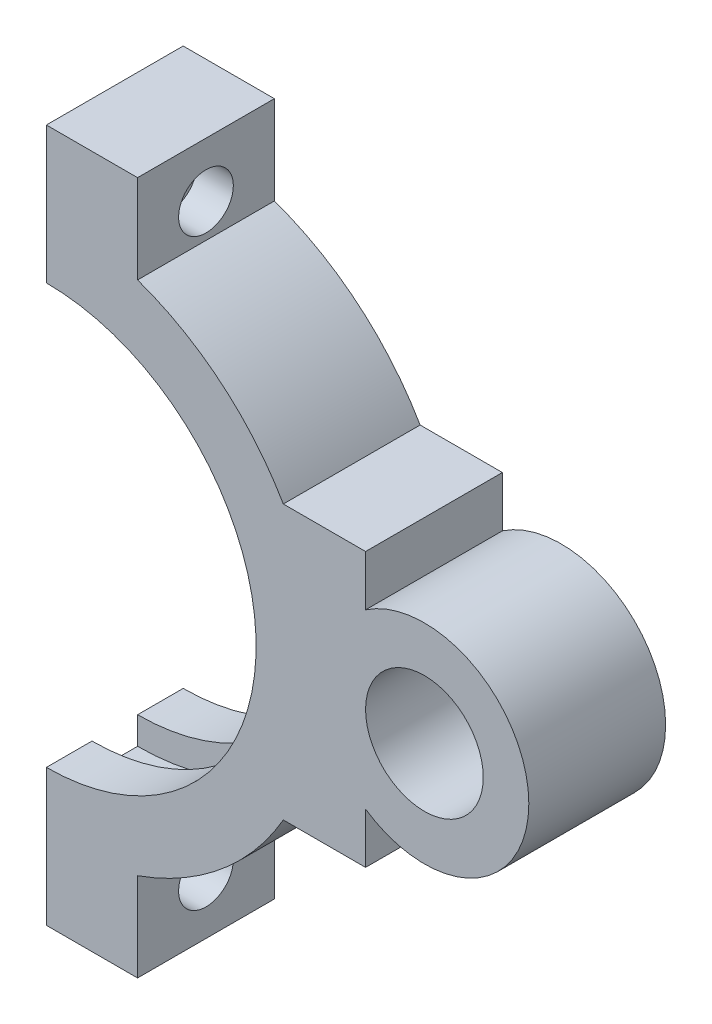
SolidWorks part; units mm, degrees
ref_plane "Front Plane" through (0, 0, 0) normal (0, 0, 1) x (1, 0, 0)
ref_plane "Top Plane" through (0, 0, 0) normal (0, 1, 0) x (1, 0, 0)
ref_plane "Right Plane" through (0, 0, 0) normal (1, 0, 0) x (0, 0, -1)
sketch "Sketch1" plane through (0, 0, 0) normal (0, 0, 1) x (1, 0, 0)
  line L0 (0, 26.4851) -> (0, 30.4851)
  line L1 (0, -25.5149) -> (0, -29.5149)
  line L2 (30, 15.4851) -> (30, -14.5149) construction
  line L3 (25.9808, 15.4851) -> (35, 15.4851)
  line L4 (25.9808, -14.5149) -> (35, -14.5149)
  line L5 (0, 0.4851) -> (66.6758, 0.4851) construction
  line L6 (35, 15.4851) -> (35, -14.5149) construction
  line L7 (35, -14.5149) -> (35, -8.9754)
  line L8 (35, 9.9455) -> (35, 15.4851)
  line L9 (0, 30.4851) -> (0, 38.4851)
  line L10 (0, 38.4851) -> (10, 38.4851)
  line L11 (10, 38.4851) -> (10, 28.7693)
  line L12 (10, -37.5149) -> (10, -27.7992)
  line L13 (0, -37.5149) -> (10, -37.5149)
  line L14 (0, -29.5149) -> (0, -37.5149)
  arc A0 (0, 26.4851) -> (0, -25.5149) centre (0, 0.4851) cw
  arc A1 (10, 28.7693) -> (25.9808, 15.4851) centre (0, 0.4851) cw
  arc A2 (25.9808, -14.5149) -> (10, -27.7992) centre (0, 0.4851) cw
  arc A3 (41.45, 6.9351) -> (41.45, -5.9649) centre (41.45, 0.4851) ccw
  arc A4 (41.45, 6.9351) -> (41.45, -5.9649) centre (41.45, 0.4851) cw
  arc A5 (35, 9.9455) -> (35, -8.9754) centre (41.45, 0.4851) cw
  point P10 (26, 0.4851)
  dimension "D1" = 26
  dimension "D6" = 4
  dimension "D7" = 180
  dimension "D8" = 6.45
  dimension "D9" = 5
  dimension "D3" = 4
  dimension "D4" = 30
  dimension "D5" = 5
  dimension "D10" = 8
  dimension "D11" = 10
extrude "Boss-Extrude1" add sketch "Sketch1" along normal blind 5
ref_plane "Plane1" through (0, 0, 5) normal (0, 0, 1) x (1, 0, 0)
sketch "Sketch2" plane through (0, 0, 5) normal (0, 0, 1) x (1, 0, 0)
  line L0 (0, 26.4851) -> (0, 23.4851)
  line L1 (0, -25.5149) -> (0, -22.5149)
  line L2 (0, 26.4851) -> (0, 30.4851)
  line L3 (0, -25.5149) -> (0, -37.5149) construction
  line L4 (0, -25.5149) -> (0, -29.5149)
  line L7 (35, -14.5149) -> (25.9808, -14.5149)
  line L8 (35, -8.9754) -> (35, -14.5149)
  line L9 (25.9808, 15.4851) -> (35, 15.4851)
  line L10 (35, 15.4851) -> (35, 9.9455)
  line L11 (0, 30.4851) -> (0, 38.4851)
  line L12 (0, 38.4851) -> (10, 38.4851)
  line L13 (10, 38.4851) -> (10, 28.7693)
  line L14 (0, -29.5149) -> (0, -37.5149)
  line L15 (0, -37.5149) -> (10, -37.5149)
  line L16 (10, -37.5149) -> (10, -27.7992)
  arc A0 (0, 23.4851) -> (0, -22.5149) centre (0, 0.4851) cw
  arc A2 (10, -27.7992) -> (25.9808, -14.5149) centre (0, 0.4851) ccw construction
  arc A3 (25.9808, -14.5149) -> (10, -27.7992) centre (0, 0.4851) cw
  arc A4 (35, 9.9455) -> (35, -8.9754) centre (41.45, 0.4851) cw
  circle A5 centre (41.45, 0.4851) radius 6.45
  arc A6 (10, 28.7693) -> (25.9808, 15.4851) centre (0, 0.4851) cw
  dimension "D1" = 3
  dimension "D2" = 3
extrude "Boss-Extrude2" add sketch "Sketch2" along normal blind 5
ref_plane "Plane2" through (0, 0, 0) normal (0, 0, -1) x (-1, 0, 0)
sketch "Sketch3" plane through (0, 0, 0) normal (0, 0, -1) x (-1, 0, 0)
  line L2 (0, -22.5149) -> (0, -29.5149)
  line L10 (0, 30.4851) -> (0, 23.4851)
  line L11 (-25.9808, 15.4851) -> (-35, 15.4851)
  line L13 (-35, -14.5149) -> (-25.9808, -14.5149)
  line L14 (-35, 15.4851) -> (-35, 9.9455)
  line L15 (-35, -14.5149) -> (-35, -8.9754)
  line L16 (0, 30.4851) -> (0, 38.4851)
  line L17 (0, 38.4851) -> (-10, 38.4851)
  line L18 (-10, 38.4851) -> (-10, 28.7693)
  line L19 (-10, -27.7992) -> (-10, -37.5149)
  line L20 (-10, -37.5149) -> (0, -37.5149)
  line L21 (0, -37.5149) -> (0, -29.5149)
  arc A1 (-25.9808, -14.5149) -> (-10, -27.7992) centre (0, 0.4851) ccw
  arc A4 (0, 23.4851) -> (0, -22.5149) centre (0, 0.4851) ccw construction
  arc A6 (0, 23.4851) -> (0, -22.5149) centre (0, 0.4851) ccw
  arc A7 (-10, 28.7693) -> (-25.9808, 15.4851) centre (0, 0.4851) ccw
  arc A8 (-35, 9.9455) -> (-35, -8.9754) centre (-41.45, 0.4851) ccw
  circle A9 centre (-41.45, 0.4851) radius 6.45
extrude "Boss-Extrude4" add sketch "Sketch3" along normal blind 5
ref_plane "Plane3" through (0, 0, 10) normal (0, 0, 1) x (1, 0, 0)
ref_plane "Plane4" through (0, 0, 0) normal (-1, 0, 0) x (0, 0, 1)
sketch "Sketch7" plane through (0, 0, 0) normal (-1, 0, 0) x (0, 0, 1)
  line L0 (2.5, 38.4851) -> (2.5, -37.5149) construction
  line L1 (-5, 0.4851) -> (10, 0.4851) construction
  line L2 (10, 38.4851) -> (-5, 38.4851) construction
  circle A0 centre (2.5, 32.4851) radius 1.6
  circle A1 centre (2.5, -31.5149) radius 1.6
  dimension "D1" = 3.2
  dimension "D2" = 6
extrude "Cut-Extrude1" cut sketch "Sketch7" against normal blind 15
ref_plane "Plane6" through (10, 0, 0) normal (1, 0, 0) x (0, 0, -1)
sketch "Sketch9" plane through (10, 0, 0) normal (1, 0, 0) x (0, 0, -1)
  circle A0 centre (-2.5, -31.5149) radius 3
  circle A1 centre (-2.5, 32.4851) radius 3
  dimension "D1" = 6
  dimension "D2" = 6
extrude "Cut-Extrude3" cut sketch "Sketch9" against normal blind 4
ref_plane "Plane7" through (52.9, 0, 0) normal (1, 0, 0) x (0, 0, -1)
